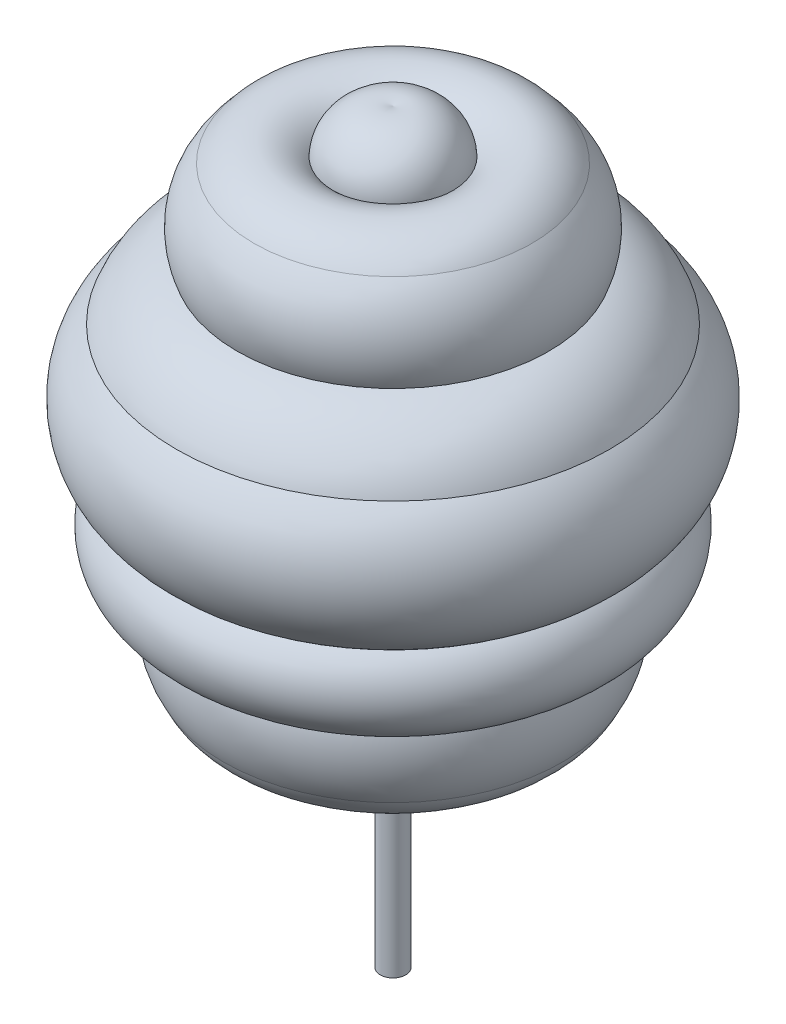
SolidWorks part; units mm, degrees
ref_plane "Front" through (0, 0, 0) normal (0, 0, 1) x (1, 0, 0)
ref_plane "Top" through (0, 0, 0) normal (0, 1, 0) x (1, 0, 0)
ref_plane "Right" through (0, 0, 0) normal (1, 0, 0) x (0, 0, -1)
sketch "Croquis1" plane through (0, 0, 0) normal (0, 1, 0) x (1, 0, 0)
  circle A0 centre (0, 0) radius 30
  dimension "D1" = 60
extrude "Saliente-Extruir1" add sketch "Croquis1" along normal mid plane 1000
sketch "Croquis2" plane through (0, 500, 0) normal (0, 1, 0) x (1, 0, 0)
  circle A0 centre (0, 0) radius 30
  dimension "D1" = 60
extrude "Saliente-Extruir2" add sketch "Croquis2" along normal blind 750 draft 1.5
sketch "Croquis4" plane through (0, 0, 0) normal (0, 0, 1) x (1, 0, 0)
  line L0 (0, 0) -> (139.4171, 0)
  line L1 (33, 0) -> (-33, 0) construction
  line L2 (0, -33) -> (0, 33) construction
  line L3 (0, 1250) -> (0, 0) construction
  line L4 (0, 0) -> (0, 1250)
  arc A0 (139.4171, 0) -> (228.1847, 54.9088) centre (139.4171, 99.2069) ccw
  arc A1 (228.1847, 54.9088) -> (397.6502, 116.0086) centre (283.7715, 166.2975) ccw
  arc A2 (397.6502, 116.0086) -> (414.5707, 287.6451) centre (216.3787, 220.5313) ccw
  arc A3 (414.5707, 287.6451) -> (486.3191, 488.8995) centre (414.3886, 401.1266) ccw
  arc A4 (486.3191, 488.8995) -> (508.3516, 806.8118) centre (371.0751, 656.6059) ccw
  arc A5 (508.3516, 806.8118) -> (365.6088, 934.596) centre (315.9805, 735.5398) ccw
  arc A6 (365.6088, 934.596) -> (325.9965, 1133.7754) centre (193.3717, 1003.8706) ccw
  arc A7 (325.9965, 1133.7754) -> (139.4171, 1147.3704) centre (226.8895, 1060.7355) ccw
  arc A8 (139.4171, 1147.3704) -> (0, 1250) centre (28.3521, 1142.5046) ccw
  point P25 (184.1214, 1116.3352)
  point P26 (283.7715, 943.7121)
  point P27 (217.7409, 1098.7035)
  point P28 (90.0745, 1184.841)
  point P29 (203.0756, 1250)
  point P30 (397.6502, 731.9641)
  point P31 (482.1786, 605.0158)
  point P32 (525.1089, 372.2773)
  point P33 (486.3191, 375.8036)
  point P34 (414.3886, 287.6451)
  point P35 (139.4171, 1142.5046)
  dimension "D1" = 1250
revolve "Revolución1" add sketch "Croquis4" angle 360 about L3
